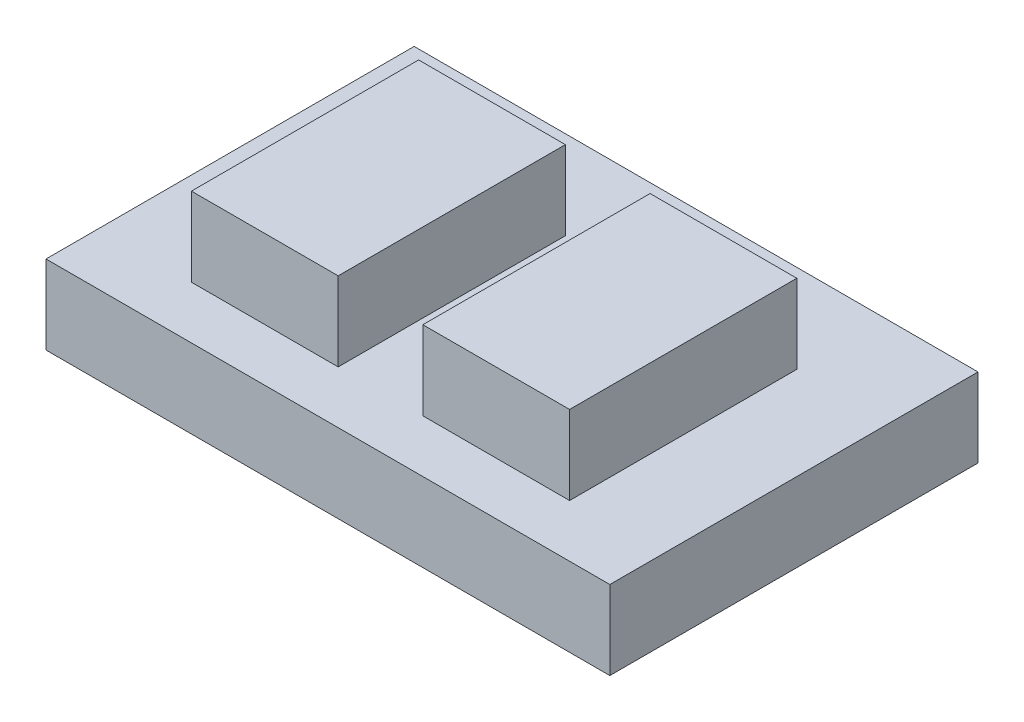
SolidWorks part; units mm, degrees
ref_plane "Front Plane" through (0, 0, 0) normal (0, 0, 1) x (1, 0, 0)
ref_plane "Top Plane" through (0, 0, 0) normal (0, 1, 0) x (1, 0, 0)
ref_plane "Right Plane" through (0, 0, 0) normal (1, 0, 0) x (0, 0, -1)
sketch "Sketch1" plane through (0, 0, 0) normal (0, 1, 0) x (1, 0, 0)
  line L0 (-5.36, 3.5) -> (-5.36, -3.5)
  line L1 (-5.36, 3.5) -> (5.36, 3.5)
  line L2 (-5.36, -3.5) -> (5.36, -3.5)
  line L3 (5.36, 3.5) -> (5.36, -3.5)
  line L4 (-5.36, 3.5) -> (5.36, -3.5) construction
  dimension "D1" = 7
  dimension "D2" = 10.72
extrude "Boss-Extrude1" add sketch "Sketch1" along normal blind 1.5
sketch "Sketch2" plane through (0, 1.5, 0) normal (0, 1, 0) x (1, 0, 0)
  line L0 (-3.595, 1.82) -> (-3.595, -2.5)
  line L1 (-3.595, 1.82) -> (-0.805, 1.82)
  line L2 (-3.595, -2.5) -> (-0.805, -2.5)
  line L3 (-0.805, 1.82) -> (-0.805, -2.5)
  line L4 (0.805, 1.82) -> (0.805, -2.5)
  line L5 (0.805, 1.82) -> (3.595, 1.82)
  line L6 (0.805, -2.5) -> (3.595, -2.5)
  line L7 (3.595, 1.82) -> (3.595, -2.5)
  line L8 (-2.2, -2.5) -> (2.2, -2.5) construction
  line L9 (-5.36, -3.5) -> (5.36, -3.5) construction
  line L10 (0, -3.5) -> (0, -2.5) construction
  dimension "D1" = 4.32
  dimension "D2" = 2.79
  dimension "D3" = 4.4
  dimension "D4" = 1
extrude "Boss-Extrude2" add sketch "Sketch2" along normal blind 1.5
